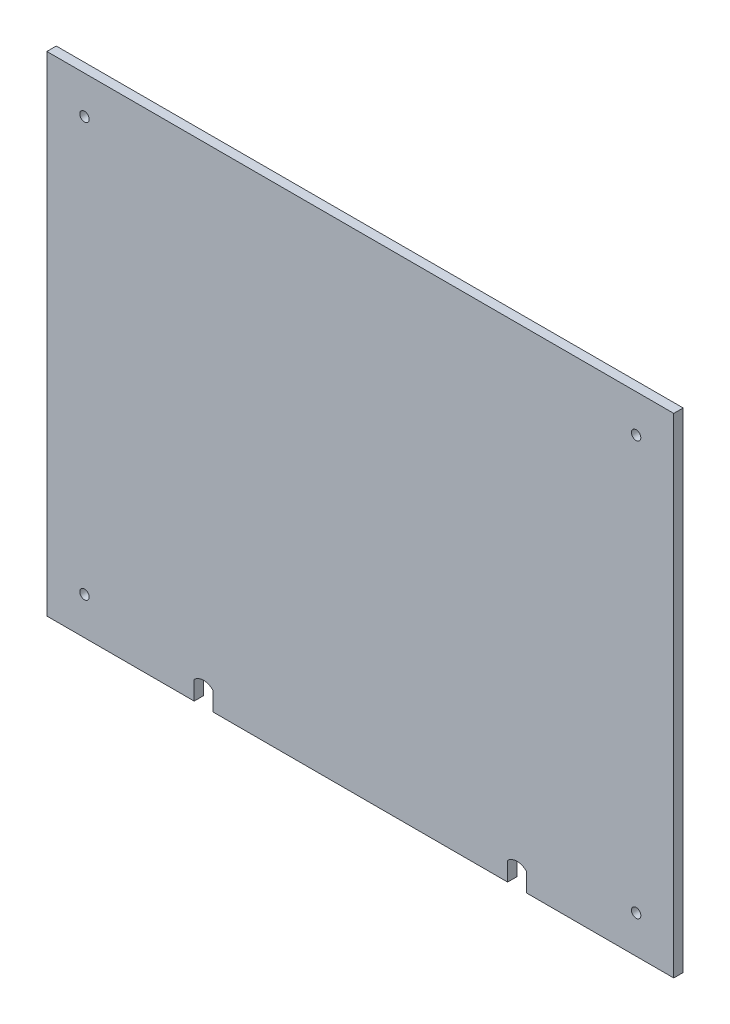
SolidWorks part; units mm, degrees
ref_plane "Front Plane" through (0, 0, 0) normal (0, 0, 1) x (1, 0, 0)
ref_plane "Top Plane" through (0, 0, 0) normal (0, 1, 0) x (1, 0, 0)
ref_plane "Right Plane" through (0, 0, 0) normal (1, 0, 0) x (0, 0, -1)
sketch "Sketch1" plane through (0, 0, 0) normal (0, 0, 1) x (1, 0, 0)
  line L0 (0, 0) -> (200, 0)
  line L1 (200, 0) -> (200, 156)
  line L2 (200, 156) -> (0, 156)
  line L3 (0, 156) -> (0, 0)
extrude "Boss-Extrude1" add sketch "Sketch1" along normal blind 3
sketch "Sketch2" plane through (0, 0, 3) normal (0, 0, 1) x (1, 0, 0)
  circle A0 centre (12, 12) radius 1.5
  circle A1 centre (12, 144) radius 1.5
  circle A2 centre (188, 144) radius 1.5
  circle A3 centre (188, 12) radius 1.5
extrude "Cut-Extrude1" cut sketch "Sketch2" against normal blind 17
sketch "Sketch6" plane through (0, 0, 3) normal (0, 0, 1) x (1, 0, 0)
  line L0 (153, 0) -> (147, 0)
  line L1 (0, 0) -> (200, 0) construction
  line L2 (153, 6) -> (153, 0)
  line L4 (147, 0) -> (147, 6)
  line L6 (53, 0) -> (53, 6)
  line L8 (47, 6) -> (47, 0)
  line L9 (47, 0) -> (53, 0)
  arc A0 (147, 6) -> (153, 6) centre (150, 3) cw
  arc A1 (53, 6) -> (47, 6) centre (50, 3) ccw
extrude "Cut-Extrude10" cut sketch "Sketch6" against normal blind 10
